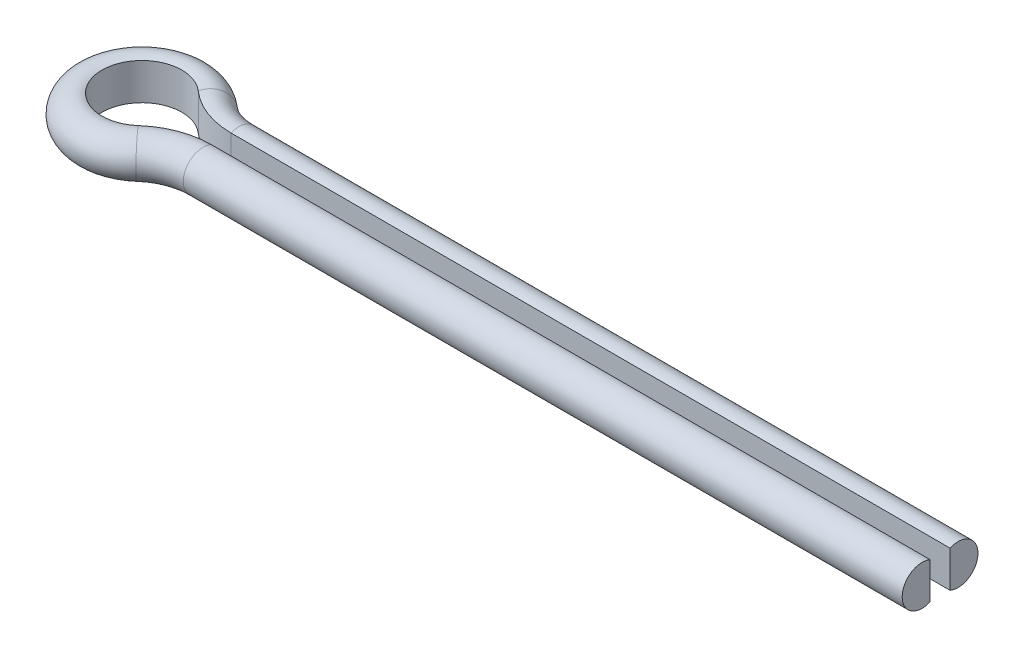
SolidWorks part; units mm, degrees
ref_plane "Front Plane" through (0, 0, 0) normal (0, 0, 1) x (1, 0, 0)
ref_plane "Top Plane" through (0, 0, 0) normal (0, 1, 0) x (1, 0, 0)
ref_plane "Right Plane" through (0, 0, 0) normal (1, 0, 0) x (0, 0, -1)
sketch "Sketch1" plane through (0, 0, 0) normal (0, 1, 0) x (1, 0, 0)
  line L0 (0, 0) -> (-90.0784, 0)
  line L2 (-90.0784, -2.5) -> (0, -2.5)
  arc A0 (-90.0784, 0) -> (-96.6928, 2.5) centre (-90.0784, 10) cw
  arc A1 (-96.6928, 2.5) -> (-96.6928, -5) centre (-100, -1.25) ccw
  arc A2 (-90.0784, -2.5) -> (-96.6928, -5) centre (-90.0784, -12.5) ccw
  point P7 (0, 0)
  point P12 (-37.8213, 6.8006)
  point P13 (0, 0)
  point P14 (-39.5064, -3.9862)
  dimension "D1" = 5
  dimension "D2" = 10
  dimension "D3" = 100
  dimension "D4" = 2.5
sketch "Sketch2" plane through (0, 0, 0) normal (1, 0, 0) x (0, 0, -1)
  line L0 (0, -2.2913) -> (0, 2.2913)
  line L1 (1, 0) -> (0, 0) construction
  arc A0 (0, -2.2913) -> (0, 2.2913) centre (1, 0) ccw
  point P1 (0, 0)
  dimension "D1" = 2.5
  dimension "D2" = 1
sweep "Sweep1" add profiles "Sketch2" path "Sketch1"
